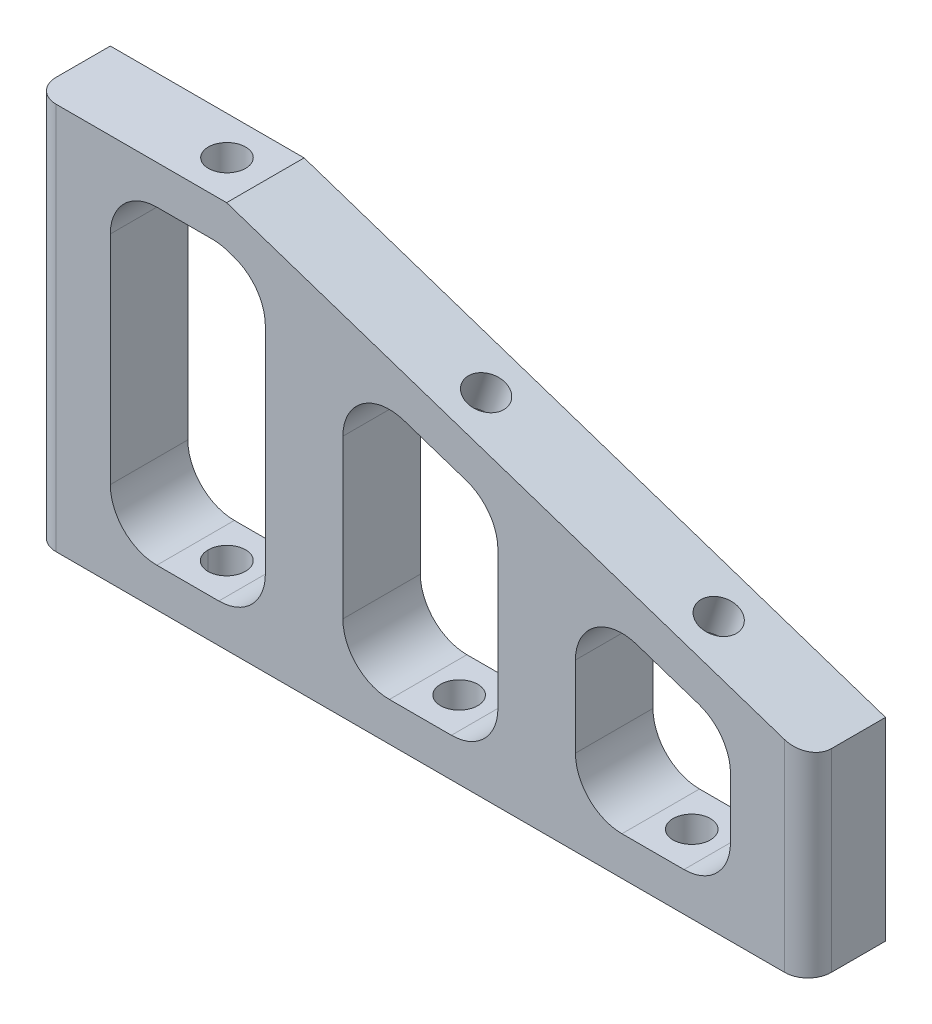
SolidWorks part; units mm, degrees
ref_plane "Plan de face" through (0, 0, 0) normal (0, 0, 1) x (1, 0, 0)
ref_plane "Plan de dessus" through (0, 0, 0) normal (0, 1, 0) x (1, 0, 0)
ref_plane "Plan de droite" through (0, 0, 0) normal (1, 0, 0) x (0, 0, -1)
sketch "Esquisse1" plane through (0, 0, 0) normal (0, 0, 1) x (1, 0, 0)
  line L0 (0, 0) -> (100, 0)
  line L1 (0, 0) -> (0, 25)
  line L2 (100, 0) -> (100, 25)
  line L3 (0, 25) -> (100, 25)
  line L4 (0, 0) -> (0, 50)
  line L5 (0, 0) -> (25, 0)
  line L6 (0, 50) -> (25, 50)
  line L7 (25, 0) -> (25, 50)
  line L8 (25, 50) -> (100, 25)
  line L9 (25, 44.7295) -> (84.1886, 25)
  line L10 (10, 45) -> (30, 45)
  line L11 (10, 45) -> (10, 5)
  line L12 (30, 45) -> (30, 5)
  line L13 (10, 5) -> (30, 5)
  line L14 (40, 5) -> (60, 5)
  line L15 (40, 5) -> (40, 45)
  line L16 (60, 5) -> (60, 45)
  line L17 (40, 45) -> (60, 45)
  line L18 (70, 45) -> (70, 5)
  line L19 (70, 45) -> (90, 45)
  line L20 (70, 5) -> (90, 5)
  line L21 (90, 45) -> (90, 5)
  line L22 (20, 0) -> (20, 45) construction
  line L23 (20, 45) -> (50, 0) construction
  line L24 (50, 0) -> (50, 45) construction
  line L25 (50, 45) -> (80, 0) construction
  line L26 (80, 0) -> (80, 45) construction
  line L27 (84.1886, 25) -> (100, 19.7295)
  line L28 (25, 44.7295) -> (9.1886, 50)
  line L29 (80, 26.3962) -> (81.5811, 31.1396) construction
  line L30 (51.5811, 41.1396) -> (50, 36.3962) construction
  point P29 (50, 45)
  point P31 (80, 45)
  point P32 (50, 0)
  dimension "D1" = 25
  dimension "D2" = 50
  dimension "D3" = 100
  dimension "D4" = 25
  dimension "D5" = 30
  dimension "D6" = 30
  dimension "D7" = 5
  dimension "D8" = 5
  dimension "D9" = 5
  dimension "D10" = 10
  dimension "D11" = 10
  dimension "D12" = 10
  dimension "D13" = 10
extrude "Boss.-Extru.1" add sketch "Esquisse1" along normal blind 10 contours L28 L10 L7 L6 | L9 L15 L8 L7 L10 L12 | L12 L10 L7 L9 | L28 L7 L10 | L10 L28 L6 L4 L3 L11 | L13 L11 L3 L1 L0 L7 | L27 L21 L20 L18 L3 L16 L14 L15 L12 L13 L7 L0 L2 | L3 L15 L9 L12 | L9 L16 L8 L15 | L18 L8 L16 L9 | L18 L9 L16 L3 | L21 L8 L18 L9 L3 | L8 L21 L3 | L21 L27 L2 L3 | L3 L27 L21
fillet "Congé1" radius 6 13 edges at (10, 45, 5) (60, 5, 5) (40, 5, 5) (90, 5, 5) (70, 5, 5) (90, 23.0629, 5) (70, 29.7295, 5) (60, 33.0629, 5) (40, 39.7295, 5) (24.1886, 45, 5) (30, 43.0629, 5) (30, 5, 5) (10, 5, 5)
sketch "Esquisse3" plane through (15.9189, 47.7566, 0) normal (-0.3162, -0.9487, 0) x (0.9487, -0.3162, 0)
  line L0 (33.7083, 10) -> (42.141, 0) construction
  line L1 (42.141, 0) -> (65.3311, 0) construction
  line L2 (65.3311, 0) -> (73.7638, 10) construction
  circle A0 centre (37.9247, 5) radius 2.4
  circle A1 centre (69.5475, 5) radius 2.4
  dimension "D1" = 4.8
  dimension "D2" = 4.8
extrude "Enlèv. mat.-Extru.1" cut sketch "Esquisse3" against normal blind 10
sketch "Esquisse4" plane through (0, 0, 0) normal (0, -1, 0) x (1, 0, 0)
  line L0 (0, 10) -> (100, 0) construction
  line L1 (100, 0) -> (100, 10) construction
  line L2 (100, 10) -> (0, 0) construction
  line L3 (0, 0) -> (0, 5) construction
  line L4 (0, 10) -> (0, 0) construction
  line L5 (0, 5) -> (100, 5) construction
  circle A0 centre (20, 5) radius 2.4
  circle A1 centre (50, 5) radius 2.4
  circle A2 centre (80, 5) radius 2.4
  dimension "D3" = 4.8
  dimension "D4" = 4.8
  dimension "D5" = 4.8
  dimension "D1" = 30
  dimension "D2" = 30
extrude "Enlèv. mat.-Extru.2" cut sketch "Esquisse4" against normal blind 10
sketch "Esquisse5" plane through (0, 50, 0) normal (0, 1, 0) x (1, 0, 0)
  line L0 (0, -5) -> (25, -5) construction
  line L1 (0, -10) -> (0, 0) construction
  line L2 (25, -10) -> (25, 0) construction
  circle A0 centre (20, -4.9507) radius 2.4
  dimension "D1" = 4.8
  dimension "D2" = 20
extrude "Enlèv. mat.-Extru.3" cut sketch "Esquisse5" against normal through all
fillet "Congé2" radius 3 2 edges at (100, 12.5, 10) (0, 25, 10)
